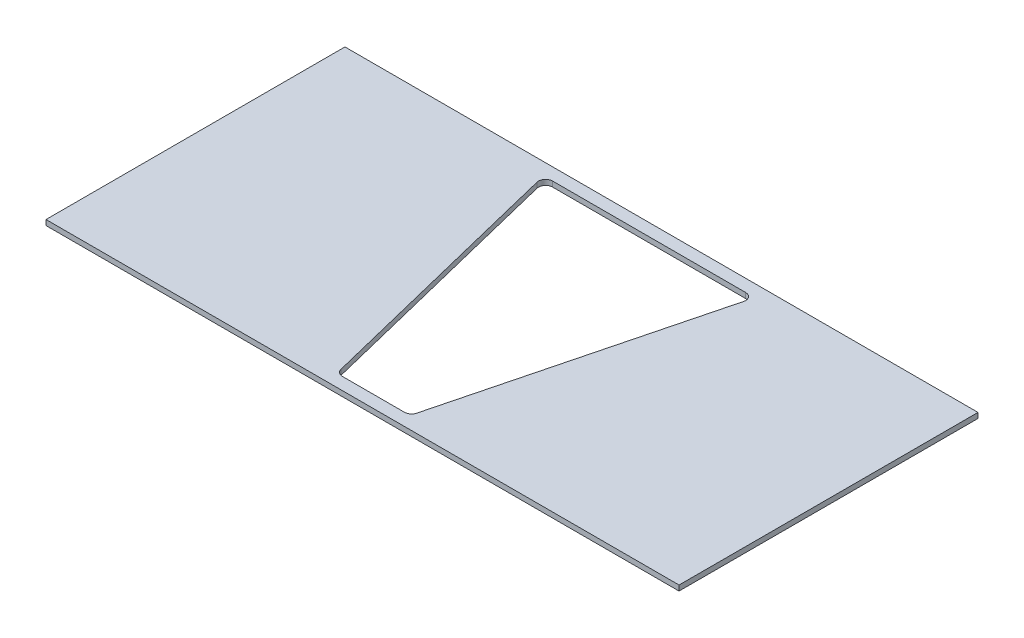
SolidWorks part; units mm, degrees
ref_plane "Front Plane" through (0, 0, 0) normal (0, 0, 1) x (1, 0, 0)
ref_plane "Top Plane" through (0, 0, 0) normal (0, 1, 0) x (1, 0, 0)
ref_plane "Right Plane" through (0, 0, 0) normal (1, 0, 0) x (0, 0, -1)
sketch "Sketch1" plane through (0, 0, 0) normal (0, 1, 0) x (1, 0, 0)
  line L1 (900, -425) -> (-900, -425)
  line L2 (900, -425) -> (900, 425)
  line L3 (900, 425) -> (-900, 425)
  line L4 (-900, -425) -> (-900, 425)
  line L5 (900, -425) -> (-900, 425) construction
  line L6 (900, 425) -> (-900, -425) construction
  point P0 (0, 0)
  dimension "D1" = 1800
  dimension "D2" = 850
extrude "Boss-Extrude1" add sketch "Sketch1" along normal mid plane 15
sketch "Sketch2" plane through (0, 7.5, 0) normal (0, 1, 0) x (1, 0, 0)
  line L0 (-300, 390) -> (300, 390)
  line L1 (300, 390) -> (100, -390)
  line L2 (100, -390) -> (-108, -390)
  line L3 (-108, -390) -> (-300, 390)
  line L4 (0, 1.7499) -> (0, 677.6104) construction
  line L5 (900, 425) -> (-900, 425) construction
  dimension "D1" = 300
  dimension "D2" = 300
  dimension "D3" = 780
  dimension "D4" = 35
  dimension "D5" = 108
  dimension "D6" = 100
extrude "Cut-Extrude1" cut sketch "Sketch2" against normal blind 480
fillet "Fillet1" radius 20 4 edges at (-108, 0, 390) (100, 0, 390) (-300, 0, -390) (300, 0, -390)
